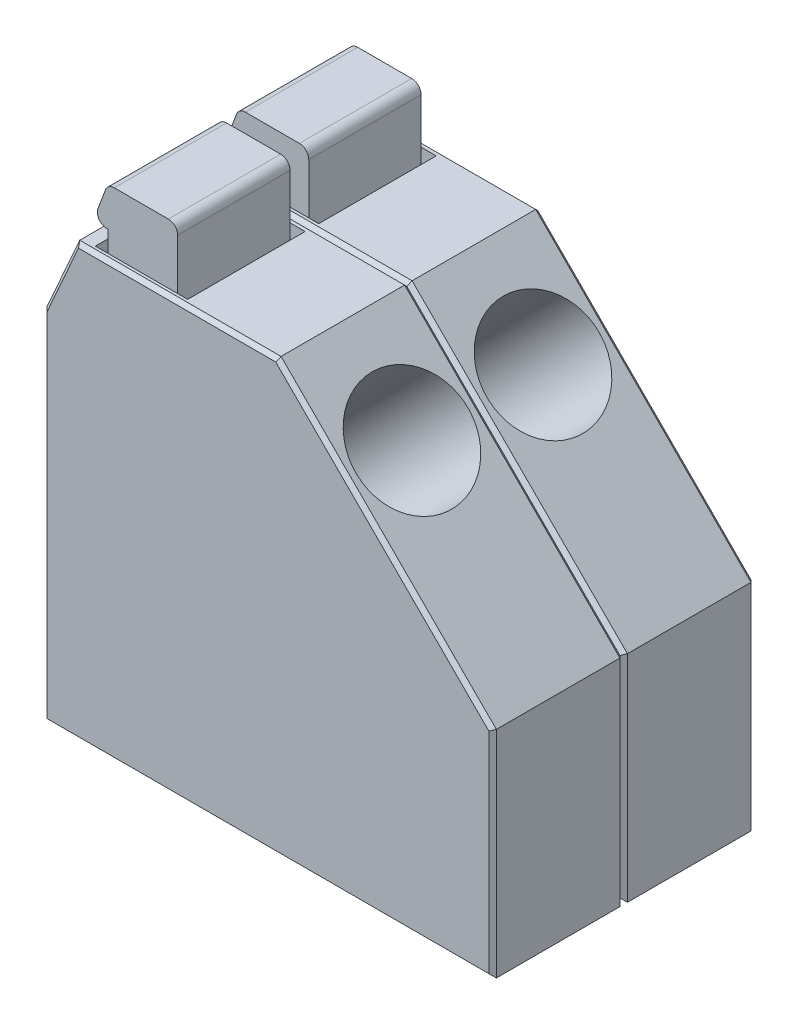
SolidWorks part; units mm, degrees
ref_plane "Front Plane" through (0, 0, 0) normal (0, 0, 1) x (1, 0, 0)
ref_plane "Top Plane" through (0, 0, 0) normal (0, 1, 0) x (1, 0, 0)
ref_plane "Right Plane" through (0, 0, 0) normal (1, 0, 0) x (0, 0, -1)
sketch "Sketch1" plane through (0, 0, 0) normal (0, 0, 1) x (1, 0, 0)
  line L0 (0, 0) -> (12, 0)
  line L1 (12, 0) -> (12, 5.75)
  line L2 (12, 5.75) -> (6.25, 11.5)
  line L3 (6.25, 11.5) -> (0.8751, 11.5)
  line L5 (0.8751, 11.5) -> (0, 9.5271)
  line L6 (0, 9.5271) -> (0, 0)
  dimension "D1" = 12
  dimension "D2" = 11.5
  dimension "D3" = 135
  dimension "D4" = 5.75
extrude "Boss-Extrude1" add sketch "Sketch1" along normal blind 3.5 contours L2 L3 L5 L6 L0 L1
sketch "Sketch2" plane through (8.875, 8.875, 0) normal (0.7071, 0.7071, 0) x (0, 0, -1)
  line L0 (-1.75, 3.7123) -> (-1.75, 1.1012) construction
  line L1 (-3.5, 3.7123) -> (0, 3.7123) construction
  circle A0 centre (-1.75, 1.1012) radius 1.5
  dimension "D1" = 3
extrude "Cut-Extrude1" cut sketch "Sketch2" against normal blind 5
sketch "Sketch3" plane through (0, 11.5, 0) normal (0, 1, 0) x (1, 0, 0)
  line L1 (1.2198, -0.1897) -> (3.6834, -0.1897)
  line L2 (1.2198, -0.1897) -> (1.2198, -3.3275)
  line L3 (1.2198, -3.3275) -> (3.6834, -3.3275)
  line L4 (3.6834, -0.1897) -> (3.6834, -3.3275)
extrude "Cut-Extrude2" cut sketch "Sketch3" against normal blind 2
sketch "Sketch5" plane through (0, 0, 3.3275) normal (0, 0, -1) x (-1, 0, 0)
  line L0 (-3.4177, 9.5) -> (-3.4177, 13.1)
  line L1 (-1.2198, 9.5) -> (-3.6834, 9.5) construction
  line L2 (-3.4177, 13.1) -> (-1.5504, 13.1)
  line L3 (-1.5504, 13.1) -> (-1.16, 12.0598)
  line L4 (-1.16, 12.0598) -> (-1.5504, 12.0598)
  line L5 (-1.5504, 12.0598) -> (-1.5504, 9.5)
  line L6 (-1.5504, 9.5) -> (-3.4177, 9.5)
  line L7 (-1.2198, 11.5) -> (-3.6834, 11.5) construction
  dimension "D1" = 1.6
extrude "Boss-Extrude2" add sketch "Sketch5" along normal blind 3 separate body
fillet "Fillet1" radius 0.25 3 edges at (1.16, 12.0598, 1.8275) (3.4177, 13.1, 1.8275) (1.5504, 13.1, 1.8275)
chamfer "Chamfer1" distance 0.1 angle 45 12 edges at (9.125, 8.625, 0) (3.5626, 11.5, 0) (0.4376, 10.5135, 0) (0, 4.7635, 0) (6, 0, 0) (12, 2.875, 0) (6, 0, 3.5) (0, 4.7635, 3.5) (0.4376, 10.5135, 3.5) (3.5626, 11.5, 3.5) (9.125, 8.625, 3.5) (12, 2.875, 3.5)
pattern_linear "LPattern1" count 2 spacing 3.5 along (0, 0, 1) of bodies 104 103
sketch "Sketch7" [suppressed] plane through (0, 0, 7) normal (0, 0, 1) x (1, 0, 0)
  line L0 (0, 9.5271) -> (0.8751, 11.5)
  line L1 (0.8751, 11.5) -> (6.25, 11.5)
  line L2 (6.25, 11.5) -> (12, 5.75)
  line L3 (12, 5.75) -> (12, 0)
  line L4 (12, 0) -> (0, 0)
  line L5 (0, 0) -> (0, 9.5271)
extrude "Boss-Extrude4" [suppressed] add sketch "Sketch7" along normal blind 1.5 separate body
sketch "Sketch8" [suppressed] plane through (0, 0, 0) normal (0, -1, 0) x (1, 0, 0)
  line L0 (0, 5.25) -> (7.3, 5.25) construction
  line L2 (0, 6.9) -> (0, 3.6) construction
  line L3 (0, 1.75) -> (2.3, 1.75) construction
  line L4 (0, 3.4) -> (0, 0.1) construction
  circle A2 centre (2.3, 5.25) radius 0.5
  circle A3 centre (7.3, 1.75) radius 0.5
  dimension "D2" = 2.3
  dimension "D3" = 5
extrude "Boss-Extrude5" [suppressed] add sketch "Sketch8" along normal blind 3.6 separate body
ref_point "Point1" [suppressed]
sketch "Sketch9" plane through (0, 0, 0) normal (0, 0, -1) x (-1, 0, 0)
  circle A0 centre (-7.8248, 2.6388) radius 0.7557
  circle A1 centre (-2.3626, 8.1308) radius 0.7557
extrude "Cut-Extrude3" cut sketch "Sketch9" against normal blind 0.2
pattern_linear "LPattern2" [suppressed] count 2 spacing 7
